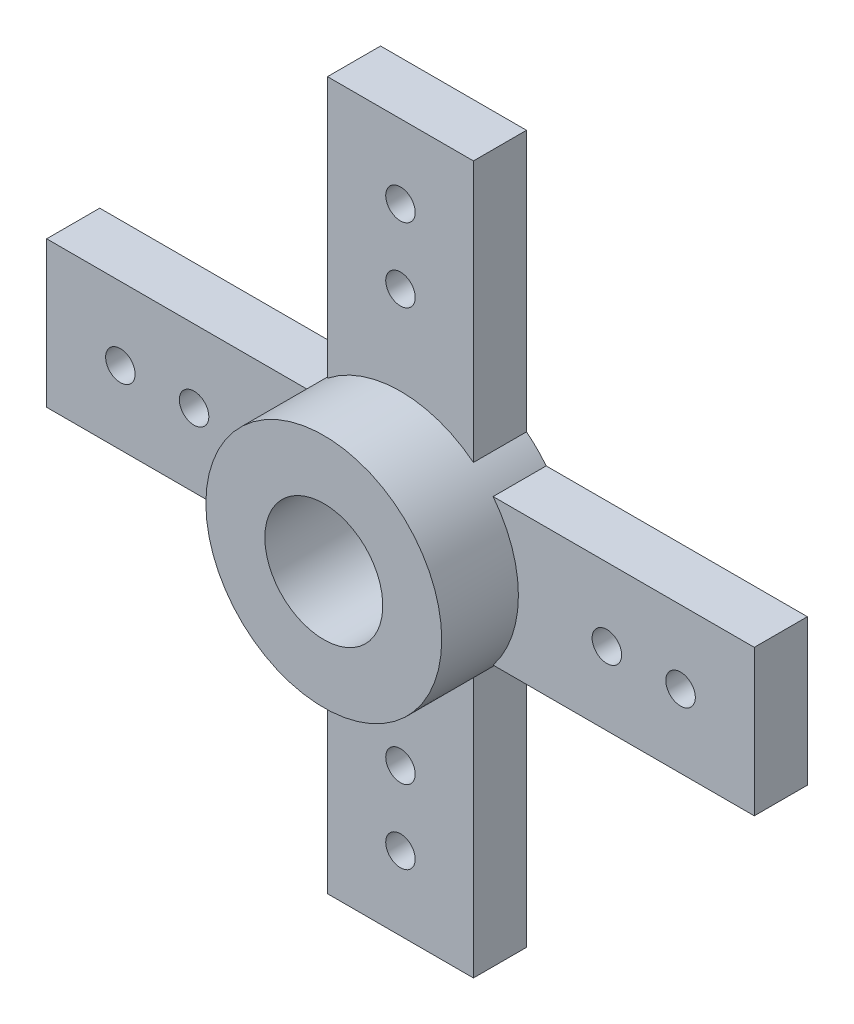
SolidWorks part; units mm, degrees
ref_plane "Front Plane" through (0, 0, 0) normal (0, 0, 1) x (1, 0, 0)
ref_plane "Top Plane" through (0, 0, 0) normal (0, 1, 0) x (1, 0, 0)
ref_plane "Right Plane" through (0, 0, 0) normal (1, 0, 0) x (0, 0, -1)
sketch "Sketch1" plane through (0, 0, 0) normal (0, 0, 1) x (1, 0, 0)
  line L0 (0, 0) -> (0, 64.7448) construction
  line L1 (-45.5327, 0) -> (34.5818, 0) construction
  line L2 (-4.6392, -4.6392) -> (3.5108, 3.5108) construction
  line L3 (-2.475, -12) -> (2.475, -12)
  line L4 (-2.475, -12) -> (-2.475, -2.475)
  line L5 (-2.475, 12) -> (2.475, 12)
  line L6 (2.475, -12) -> (2.475, -2.475)
  line L7 (12, -2.475) -> (12, 2.475)
  line L8 (-12, -2.475) -> (-12, 2.475)
  line L9 (-12, 2.475) -> (-2.475, 2.475)
  line L10 (-12, -2.475) -> (-2.475, -2.475)
  line L11 (-2.475, 2.475) -> (-2.475, 12)
  line L12 (2.475, 2.475) -> (12, 2.475)
  line L13 (2.475, -2.475) -> (12, -2.475)
  line L14 (2.475, 2.475) -> (2.475, 12)
  circle A0 centre (0, 9.5) radius 0.5
  circle A1 centre (0, 7) radius 0.5
  circle A2 centre (0, -9.5) radius 0.5
  circle A3 centre (0, -7) radius 0.5
  circle A4 centre (-9.5, 0) radius 0.5
  circle A5 centre (-7, 0) radius 0.5
  circle A6 centre (9.5, 0) radius 0.5
  circle A7 centre (7, 0) radius 0.5
  dimension "D4" = 14
  dimension "D5" = 1
  dimension "D1" = 24
  dimension "D2" = 4.95
  dimension "D3" = 2.5
  dimension "D6" = 45
extrude "Boss-Extrude1" add sketch "Sketch1" along normal blind 1.8
sketch "Sketch2" plane through (0, 0, 1.8) normal (0, 0, 1) x (1, 0, 0)
  circle A0 centre (0, 0) radius 4
  dimension "D1" = 8
extrude "Boss-Extrude2" add sketch "Sketch2" along normal blind 2.6 and the other way up to surface other way up to face at (9, 0, 0)
sketch "Sketch3" plane through (0, 0, 0) normal (0, 0, -1) x (-1, 0, 0)
  circle A0 centre (0, 0) radius 2
  dimension "D1" = 4
extrude "Cut-Extrude1" cut sketch "Sketch3" against normal through all
